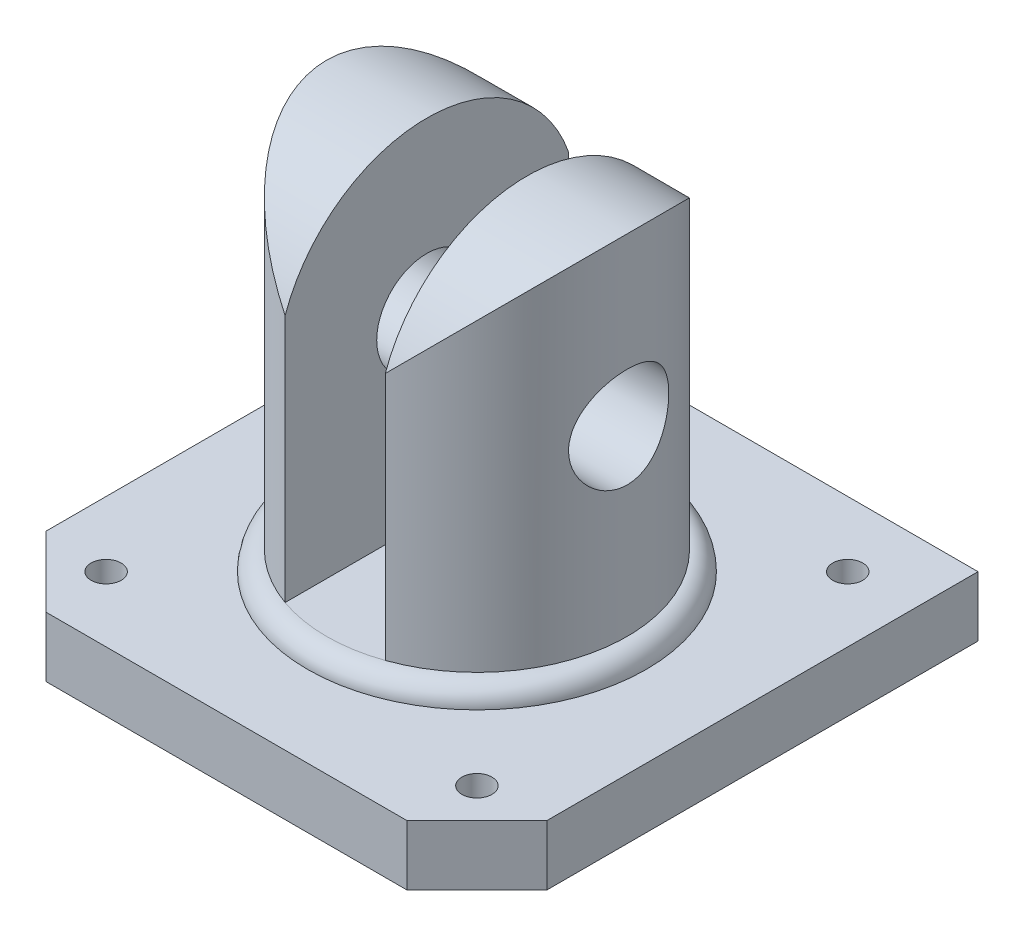
SolidWorks part; units mm, degrees
ref_plane "Front Plane" through (0, 0, 0) normal (0, 0, 1) x (1, 0, 0)
ref_plane "Top Plane" through (0, 0, 0) normal (0, 1, 0) x (1, 0, 0)
ref_plane "Right Plane" through (0, 0, 0) normal (1, 0, 0) x (0, 0, -1)
sketch "Sketch1" plane through (0, 0, 0) normal (0, 1, 0) x (1, 0, 0)
  line L1 (-25, 25) -> (25, 25)
  line L2 (-25, 25) -> (-25, -25)
  line L3 (-25, -25) -> (25, -25)
  line L4 (25, 25) -> (25, -25)
  line L5 (-25, 25) -> (25, -25) construction
  line L6 (-25, -25) -> (25, 25) construction
  point P0 (0, 0)
  dimension "D1" = 50
extrude "Boss-Extrude1" add sketch "Sketch1" along normal blind 6
sketch "Sketch2" plane through (0, 6, 0) normal (0, 1, 0) x (1, 0, 0)
  circle A0 centre (0, 0) radius 15
  dimension "D1" = 30
extrude "Boss-Extrude2" add sketch "Sketch2" along normal blind 36.7
chamfer "Chamfer1" distance 7 angle 45 1 edges at (25, 3, 25)
sketch "Sketch3" plane through (0, 0, 0) normal (0, 0, 1) x (1, 0, 0)
  line L0 (0, 43.628) -> (0, -1.9726) construction
  line L1 (-5, 43.628) -> (-5, 7.9)
  line L2 (5, 43.628) -> (5, 7.9)
  line L3 (-5, 7.9) -> (5, 7.9)
  line L4 (15, 42.7) -> (-15, 42.7) construction
  line L5 (5, 43.628) -> (5, -1.9726) construction
  line L6 (-5, 43.628) -> (-5, -1.9726) construction
  line L7 (5, 43.628) -> (-5, 43.628)
  dimension "D1" = 5
  dimension "D3" = 34.8
  dimension "D2" = 5
extrude "Cut-Extrude1" cut sketch "Sketch3" against normal blind 36.7 and the other way blind 36.7
sketch "Sketch4" plane through (0, 0, 0) normal (1, 0, 0) x (0, 0, -1)
  line L0 (14.1421, 42.7) -> (-14.1421, 42.7) construction
  line L1 (-14.376, 31.9814) -> (-17.2812, 49.2898)
  line L2 (-17.2812, 49.2898) -> (26.2243, 49.2898)
  line L3 (26.2243, 49.2898) -> (14.4755, 31.632)
  arc A0 (14.4755, 31.632) -> (-14.376, 31.9814) centre (0, 27.7) ccw
  dimension "D1" = 30
extrude "Cut-Extrude2" cut sketch "Sketch4" against normal blind 36.7 and the other way blind 36.7
sketch "Sketch5" plane through (0, 0, 0) normal (1, 0, 0) x (0, 0, -1)
  line L0 (-18, 6) -> (25, 6) construction
  circle A0 centre (0, 26) radius 5
  dimension "D1" = 10
  dimension "D2" = 20
extrude "Cut-Extrude3" cut sketch "Sketch5" against normal blind 36.7 and the other way blind 36.7
ref_axis "Axis1" through (0, 42.7, 0) along (0, -1, 0)
sketch "Sketch6" plane through (0, 0, 0) normal (1, 0, 0) x (0, 0, -1)
  line L0 (-15, 7.9) -> (-15, 6)
  line L1 (-15, 6) -> (-16.9, 6)
  arc A0 (-15, 7.9) -> (-16.9, 6) centre (-15, 6) ccw
revolve "Revolve1" add sketch "Sketch6" angle 360 about axis through (0, 42.7, 0) along (0, -1, 0)
sketch "Sketch7" plane through (0, 6, 0) normal (0, 1, 0) x (1, 0, 0)
  line L1 (-18.5, -18.5) -> (18.5, -18.5) construction
  line L2 (-18.5, -18.5) -> (-18.5, 18.5) construction
  line L3 (-18.5, 18.5) -> (18.5, 18.5) construction
  line L4 (18.5, -18.5) -> (18.5, 18.5) construction
  line L5 (-18.5, -18.5) -> (18.5, 18.5) construction
  line L6 (-18.5, 18.5) -> (18.5, -18.5) construction
  circle A0 centre (-18.5, 18.5) radius 1.5
  circle A1 centre (18.5, 18.5) radius 1.5
  circle A2 centre (18.5, -18.5) radius 1.5
  circle A3 centre (-18.5, -18.5) radius 1.5
  point P0 (0, 0)
  dimension "D2" = 3
  dimension "D3" = 3
  dimension "D4" = 3
  dimension "D5" = 3
  dimension "D1" = 37
extrude "Cut-Extrude4" cut sketch "Sketch7" against normal blind 9
chamfer "Chamfer2" distance 7 angle 45 1 edges at (-25, 3, 25)
